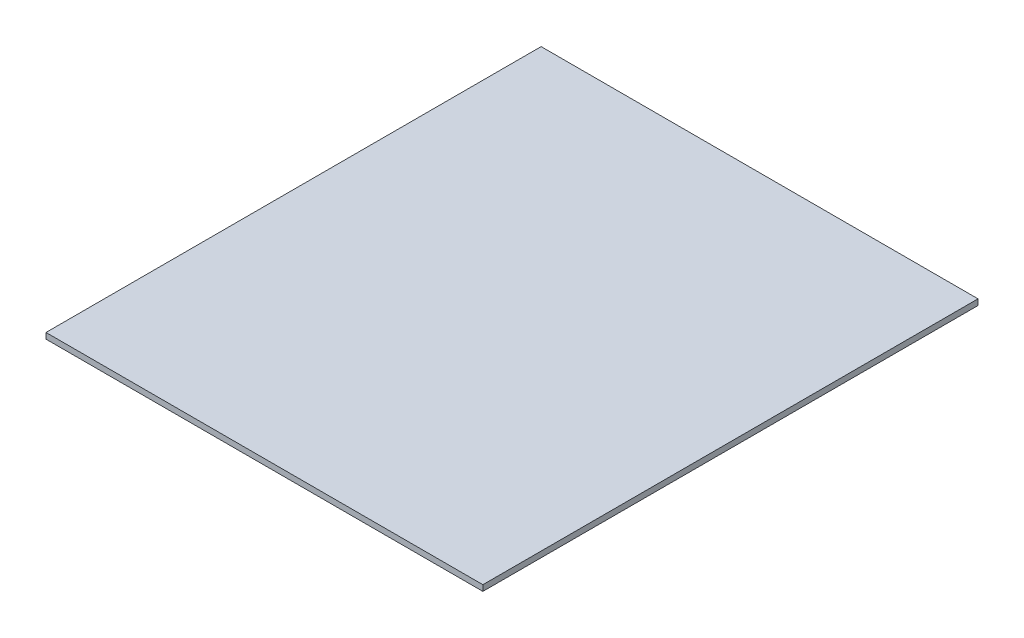
SolidWorks part; units mm, degrees
ref_plane "Front Plane" through (0, 0, 0) normal (0, 0, 1) x (1, 0, 0)
ref_plane "Top Plane" through (0, 0, 0) normal (0, 1, 0) x (1, 0, 0)
ref_plane "Right Plane" through (0, 0, 0) normal (1, 0, 0) x (0, 0, -1)
sketch "Sketch1" plane through (0, 0, 0) normal (0, 1, 0) x (1, 0, 0)
  line L1 (-70.2094, -105.463) -> (79.7906, -105.463)
  line L2 (-70.2094, -105.463) -> (-70.2094, 64.537)
  line L3 (-70.2094, 64.537) -> (79.7906, 64.537)
  line L4 (79.7906, -105.463) -> (79.7906, 64.537)
  dimension "D1" = 150
  dimension "D2" = 170
extrude "Boss-Extrude1" add sketch "Sketch1" along normal blind 2
